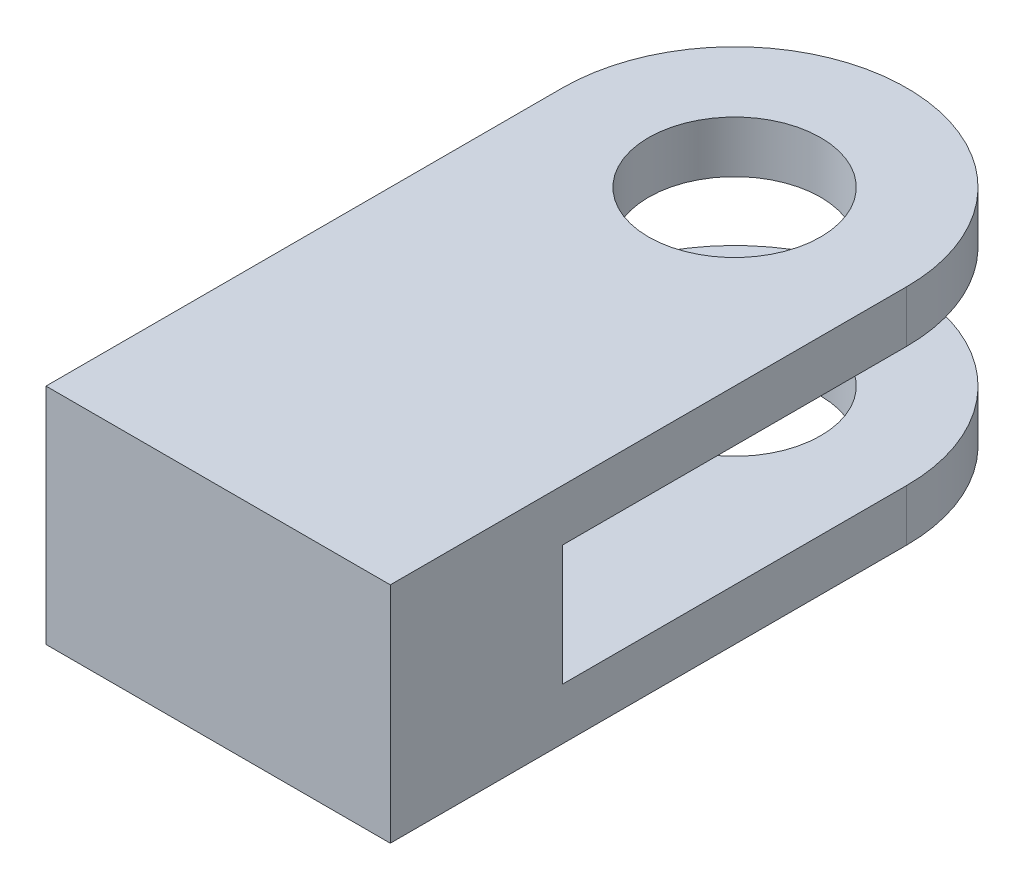
SolidWorks part; units mm, degrees
material "ABS"
ref_plane "Plan de face" through (0, 0, 0) normal (0, 0, 1) x (1, 0, 0)
ref_plane "Plan de dessus" through (0, 0, 0) normal (0, 1, 0) x (1, 0, 0)
ref_plane "Plan de droite" through (0, 0, 0) normal (1, 0, 0) x (0, 0, -1)
sketch "Esquisse3" plane through (0, 0, 0) normal (0, 1, 0) x (1, 0, 0)
  line L0 (-10, -30) -> (-10, 0)
  line L1 (10, 0) -> (10, -30)
  line L2 (10, -30) -> (-10, -30)
  arc A0 (-10, 0) -> (10, 0) centre (0, 0) cw
  dimension "D1" = 10
  dimension "D2" = 30
extrude "Boss.-Extru.1" add sketch "Esquisse3" along normal mid plane 13
sketch "Esquisse4" plane through (0, 0, 0) normal (0, 0, 1) x (1, 0, 0)
  line L0 (10, 6.5) -> (10, -6.5) construction
  line L1 (-10, -3.5) -> (10, -3.5)
  line L2 (-10, -3.5) -> (-10, 3.5)
  line L3 (-10, 3.5) -> (10, 3.5)
  line L4 (10, -3.5) -> (10, 3.5)
  line L5 (-10, -3.5) -> (10, 3.5) construction
  line L6 (-10, 3.5) -> (10, -3.5) construction
  line L7 (-10, 6.5) -> (10, 6.5) construction
  point P0 (0, 0)
  dimension "D1" = 3
extrude "Enlèv. mat.-Extru.1" cut sketch "Esquisse4" against normal through all and the other way blind 20
sketch "Esquisse5" plane through (0, 6.5, 0) normal (0, 1, 0) x (1, 0, 0)
  circle A0 centre (0, 0) radius 5
extrude "Enlèv. mat.-Extru.2" cut sketch "Esquisse5" against normal through all
